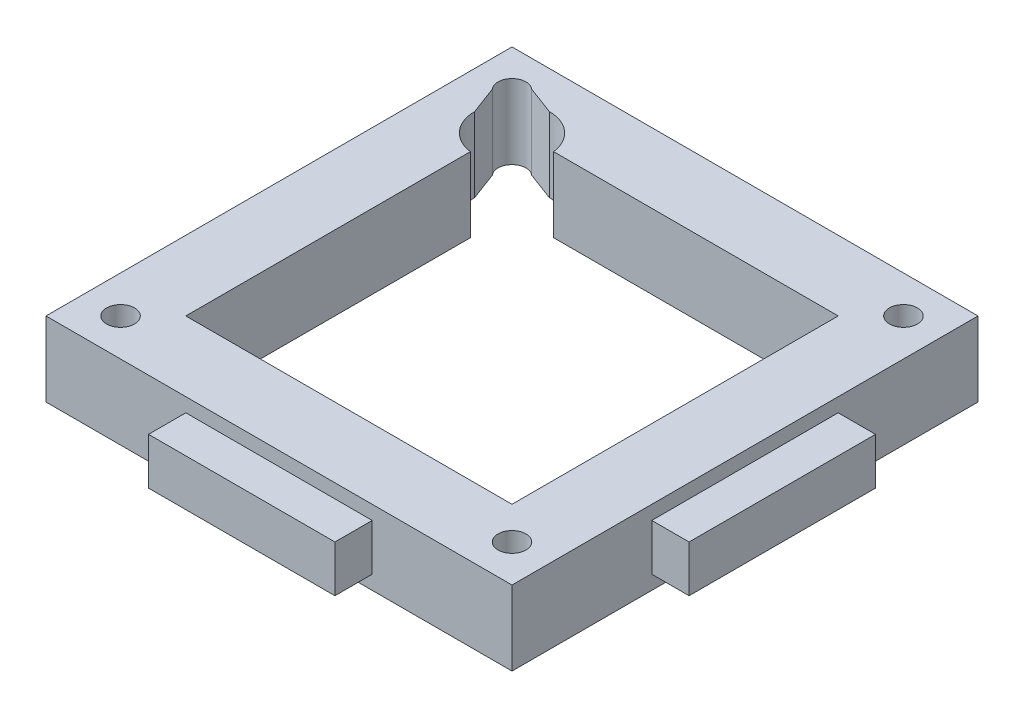
SolidWorks part; units mm, degrees
ref_plane "Front Plane" through (0, 0, 0) normal (0, 0, 1) x (1, 0, 0)
ref_plane "Top Plane" through (0, 0, 0) normal (0, 1, 0) x (1, 0, 0)
ref_plane "Right Plane" through (0, 0, 0) normal (1, 0, 0) x (0, 0, -1)
sketch "Sketch1" plane through (0, 0, 0) normal (0, 1, 0) x (1, 0, 0)
  line L0 (17.5, 17.5) -> (-13.0314, 17.5)
  line L1 (-25, -25) -> (25, -25)
  line L2 (-25, -25) -> (-25, 25)
  line L3 (-25, 25) -> (25, 25)
  line L4 (25, -25) -> (25, 25)
  line L5 (0, 25) -> (0, -25) construction
  line L6 (-25, 0) -> (25, 0) construction
  line L11 (0, 20) -> (0, -20) construction
  line L12 (-20, 0) -> (20, 0) construction
  line L13 (-17.5, -17.5) -> (17.5, -17.5)
  line L16 (17.5, -17.5) -> (17.5, 17.5)
  line L17 (0, 17.5) -> (0, -17.5) construction
  line L18 (-17.5, 0) -> (17.5, 0) construction
  line L19 (-17.5, -17.5) -> (-17.5, 13.0314)
  line L20 (-22.1301, 20.0137) -> (-21, 17)
  line L21 (-20.0137, 22.1301) -> (-17, 21)
  arc A0 (-20.0137, 22.1301) -> (-22.1301, 20.0137) centre (-21, 21) ccw
  circle A1 centre (21, 21) radius 1.5
  circle A2 centre (21, -21) radius 1.5
  circle A3 centre (-21, -21) radius 1.5
  arc A4 (-21, 17) -> (-17, 21) centre (-17, 17) ccw
  point P0 (0, 0)
  point P4 (0, 0)
  point P13 (0, 0)
  dimension "D1" = 50
  dimension "D2" = 50
  dimension "D4" = 35
extrude "Support" add sketch "Sketch1" along normal blind 8 contours L1 L4 L3 L2 A4 L0 L16 L13 L19 L20 A0 L21 A1 A2 A3
sketch "Sketch2" plane through (0, 0, 0) normal (0, 0, 1) x (1, 0, 0)
  line L4 (-10, 1.5) -> (10, 1.5)
  line L5 (-10, 1.5) -> (-10, 6.5)
  line L6 (-10, 6.5) -> (10, 6.5)
  line L7 (10, 1.5) -> (10, 6.5)
  line L8 (0, 6.5) -> (0, 1.5) construction
  line L9 (-10, 4) -> (10, 4) construction
  point P6 (0, 4)
  dimension "D1" = 20
  dimension "D2" = 5
extrude "South Dowel" add sketch "Sketch2" along normal blind 4 from surface at 25 starting at face at (0, 4, 25)
sketch "Sketch3" plane through (0, 0, 0) normal (1, 0, 0) x (0, 0, -1)
  line L4 (-10, 1.5) -> (10, 1.5)
  line L5 (-10, 1.5) -> (-10, 6.5)
  line L6 (-10, 6.5) -> (10, 6.5)
  line L7 (10, 1.5) -> (10, 6.5)
  line L8 (0, 6.5) -> (0, 1.5) construction
  line L9 (-10, 4) -> (10, 4) construction
  point P6 (0, 4)
  dimension "D1" = 20
  dimension "D2" = 5
extrude "West Dowel" add sketch "Sketch3" along normal blind 4 from surface at 25 starting at face at (25, 4, 0)
